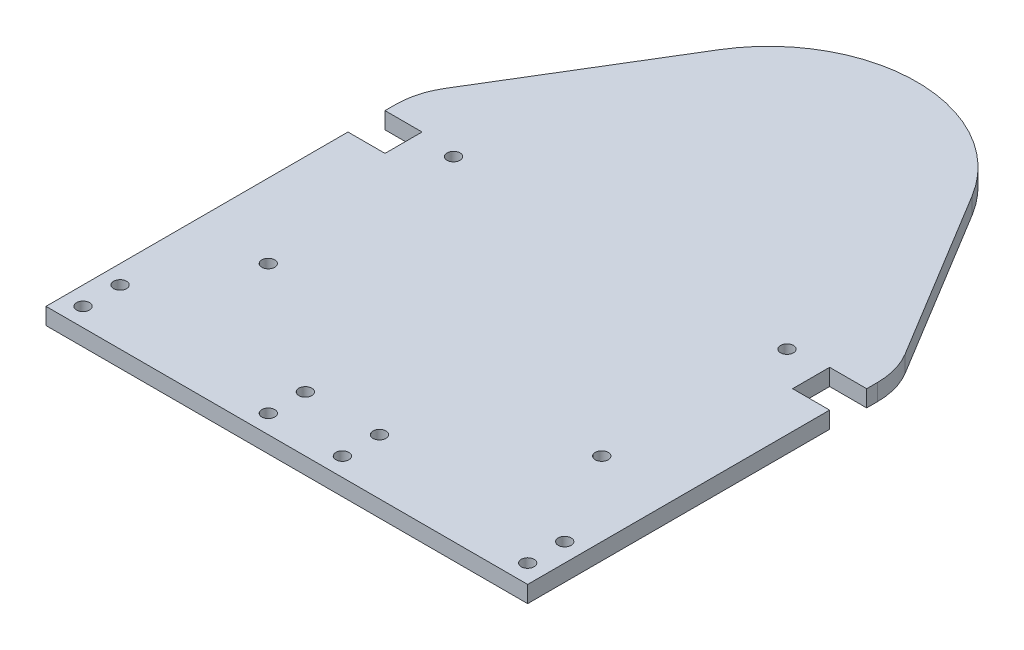
SolidWorks part; units mm, degrees
ref_plane "정면" through (0, 0, 0) normal (0, 0, 1) x (1, 0, 0)
ref_plane "윗면" through (0, 0, 0) normal (0, 1, 0) x (1, 0, 0)
ref_plane "우측면" through (0, 0, 0) normal (1, 0, 0) x (0, 0, -1)
sketch "스케치1" plane through (0, 0, 0) normal (0, 1, 0) x (1, 0, 0)
  line L0 (-65, 25) -> (-34.1944, 75.7544)
  line L2 (-65, 25) -> (-65, -75)
  line L3 (-65, -75) -> (65, -75)
  line L4 (65, 25) -> (65, -75)
  line L7 (65, 25) -> (34.1944, 75.7544)
  arc A0 (34.1944, 75.7544) -> (-34.1944, 75.7544) centre (0, 55) ccw
  point P0 (0, 0)
  point P4 (0, -75)
  dimension "D2" = 80
  dimension "D4" = 130
  dimension "D1" = 100
  dimension "D3" = 130
extrude "보스-돌출1" add sketch "스케치1" along normal blind 4.5
fillet "필렛1" radius 20 2 edges at (65, 2.25, -25) (-65, 2.25, -25)
sketch "스케치2" plane through (0, 4.5, 0) normal (0, 1, 0) x (1, 0, 0)
  line L0 (-65, 19.4054) -> (-65, -75) construction
  line L1 (-65, 16.5) -> (-55, 16.5)
  line L2 (-65, 16.5) -> (-65, 6.5)
  line L3 (-65, 6.5) -> (-55, 6.5)
  line L4 (-55, 16.5) -> (-55, 6.5)
  line L5 (65, -75) -> (65, 19.4054) construction
  line L6 (65, 16.5) -> (55, 16.5)
  line L7 (65, 16.5) -> (65, 6.5)
  line L8 (65, 6.5) -> (55, 6.5)
  line L9 (55, 16.5) -> (55, 6.5)
  line L10 (-65, -75) -> (65, -75) construction
  dimension "D1" = 10
  dimension "D2" = 10
  dimension "D3" = 81.5
extrude "컷-돌출1" cut sketch "스케치2" against normal through all
sketch "스케치3" plane through (0, 4.5, 0) normal (0, 1, 0) x (1, 0, 0)
  line L0 (-65, -75) -> (65, -75) construction
  line L1 (-60, -70) -> (60, -70) construction
  line L2 (-60, -70) -> (-60, -60) construction
  line L3 (-60, -60) -> (60, -60) construction
  line L4 (60, -70) -> (60, -60) construction
  line L5 (65, -75) -> (65, 6.5) construction
  line L6 (-65, 6.5) -> (-65, -75) construction
  line L7 (-45, 15) -> (45, 15) construction
  line L8 (-10, -60) -> (10, -60) construction
  line L9 (-10, -60) -> (-10, -70) construction
  line L10 (-10, -70) -> (10, -70) construction
  line L11 (10, -60) -> (10, -70) construction
  line L12 (-45, 15) -> (-45, -35) construction
  line L13 (-45, -35) -> (45, -35) construction
  line L14 (45, 15) -> (45, -35) construction
  circle A0 centre (-60, -60) radius 1.75
  circle A1 centre (-60, -70) radius 1.75
  circle A2 centre (60, -60) radius 1.75
  circle A3 centre (60, -70) radius 1.75
  circle A4 centre (-10, -60) radius 1.75
  circle A5 centre (10, -60) radius 1.75
  circle A6 centre (-10, -70) radius 1.75
  circle A7 centre (10, -70) radius 1.75
  circle A8 centre (-45, 15) radius 1.75
  circle A9 centre (45, 15) radius 1.75
  circle A10 centre (-45, -35) radius 1.75
  circle A11 centre (45, -35) radius 1.75
  dimension "D7" = 3.5
  dimension "D11" = 3.5
  dimension "D1" = 120
  dimension "D2" = 10
  dimension "D3" = 5
  dimension "D4" = 5
  dimension "D5" = 20
  dimension "D6" = 50
  dimension "D8" = 20
  dimension "D9" = 20
  dimension "D10" = 50
  dimension "D12" = 25
extrude "컷-돌출2" cut sketch "스케치3" against normal through all
